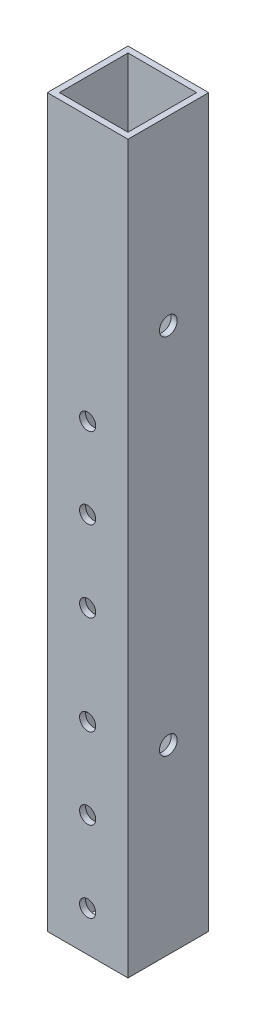
SolidWorks part; units mm, degrees
ref_plane "前视基准面" through (0, 0, 0) normal (0, 0, 1) x (1, 0, 0)
ref_plane "上视基准面" through (0, 0, 0) normal (0, 1, 0) x (1, 0, 0)
ref_plane "右视基准面" through (0, 0, 0) normal (1, 0, 0) x (0, 0, -1)
other "Configuration Table"
sketch "草图1" plane through (0, 0, 0) normal (0, 1, 0) x (1, 0, 0)
  line L1 (-8.5, 8.5) -> (8.5, 8.5)
  line L2 (-8.5, 8.5) -> (-8.5, -8.5)
  line L3 (-8.5, -8.5) -> (8.5, -8.5)
  line L4 (8.5, 8.5) -> (8.5, -8.5)
  line L5 (-8.5, 8.5) -> (8.5, -8.5) construction
  line L6 (-8.5, -8.5) -> (8.5, 8.5) construction
  line L7 (-10, 10) -> (10, 10)
  line L8 (-10, 10) -> (-10, -10)
  line L9 (-10, -10) -> (10, -10)
  line L10 (10, 10) -> (10, -10)
  line L11 (-10, 10) -> (10, -10) construction
  line L12 (-10, -10) -> (10, 10) construction
  point P0 (0, 0)
  point P5 (0, 0)
  dimension "D1" = 20
  dimension "D2" = 1.5
extrude "凸台-拉伸1" add sketch "草图1" along normal blind 180
sketch "草图2" plane through (10, 0, 0) normal (1, 0, 0) x (0, 0, -1)
  line L0 (-10, 90) -> (0, 90) construction
  line L1 (-10, 180) -> (-10, 0) construction
  line L2 (0, 90) -> (0, 135) construction
  circle A0 centre (0, 135) radius 2.2
  circle A1 centre (0, 45) radius 2.2
  dimension "D2" = 4.4
  dimension "D1" = 45
extrude "切除-拉伸1" cut sketch "草图2" against normal blind 120
sketch "草图3" plane through (0, 0, 10) normal (0, 0, 1) x (1, 0, 0)
  line L0 (0, 0) -> (0, 10) construction
  circle A1 centre (0, 10) radius 2
  circle A2 centre (0, 30) radius 2
  circle A3 centre (0, 50) radius 2
  dimension "D1" = 4
  dimension "D4" = 20
  dimension "D2" = 10
  dimension "D3" = 3
extrude "切除-拉伸2" cut sketch "草图3" against normal blind 3
sketch "草图4" plane through (0, 0, 10) normal (0, 0, 1) x (1, 0, 0)
  line L0 (0, 50) -> (0, 74.45) construction
  line L1 (0, 73.9633) -> (0, 87.9512) construction
  circle A0 centre (0, 74.45) radius 2
  circle A1 centre (0, 94.45) radius 2
  circle A2 centre (0, 114.45) radius 2
  dimension "D2" = 4
  dimension "D4" = 20
  dimension "D1" = 24.45
  dimension "D3" = 3
extrude "切除-拉伸3" cut sketch "草图4" against normal blind 20
